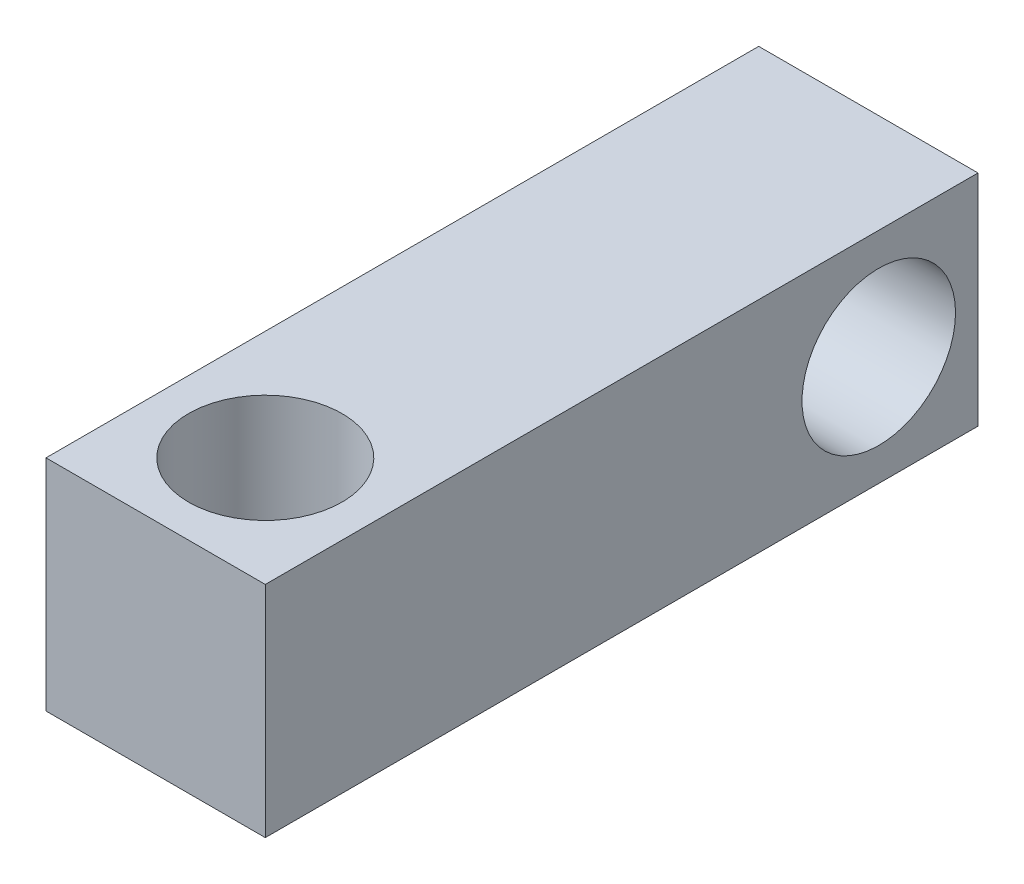
SolidWorks part; units mm, degrees
ref_plane "Płaszczyzna przednia" through (0, 0, 0) normal (0, 0, 1) x (1, 0, 0)
ref_plane "Płaszczyzna górna" through (0, 0, 0) normal (0, 1, 0) x (1, 0, 0)
ref_plane "Płaszczyzna prawa" through (0, 0, 0) normal (1, 0, 0) x (0, 0, -1)
sketch "Szkic1" plane through (0, 0, 0) normal (0, 0, 1) x (1, 0, 0)
  line L1 (-10, -10) -> (10, -10)
  line L2 (-10, -10) -> (-10, 10)
  line L3 (-10, 10) -> (10, 10)
  line L4 (10, -10) -> (10, 10)
  line L5 (-10, -10) -> (10, 10) construction
  line L6 (-10, 10) -> (10, -10) construction
  point P0 (0, 0)
  dimension "D1" = 20
  dimension "D2" = 20
extrude "Dodanie-wyciągnięcie1" add sketch "Szkic1" along normal blind 65
sketch "Szkic2" plane through (10, 0, 0) normal (1, 0, 0) x (0, 0, -1)
  circle A0 centre (-9.0501, 0) radius 7
extrude "Wytnij-wyciągnięcie1" cut sketch "Szkic2" against normal blind 50
sketch "Szkic3" plane through (0, 10, 0) normal (0, 1, 0) x (1, 0, 0)
  line L0 (10, -65) -> (-10, -65) construction
  circle A0 centre (0, -55) radius 7
  dimension "D1" = 10
extrude "Wytnij-wyciągnięcie2" cut sketch "Szkic3" against normal blind 50
